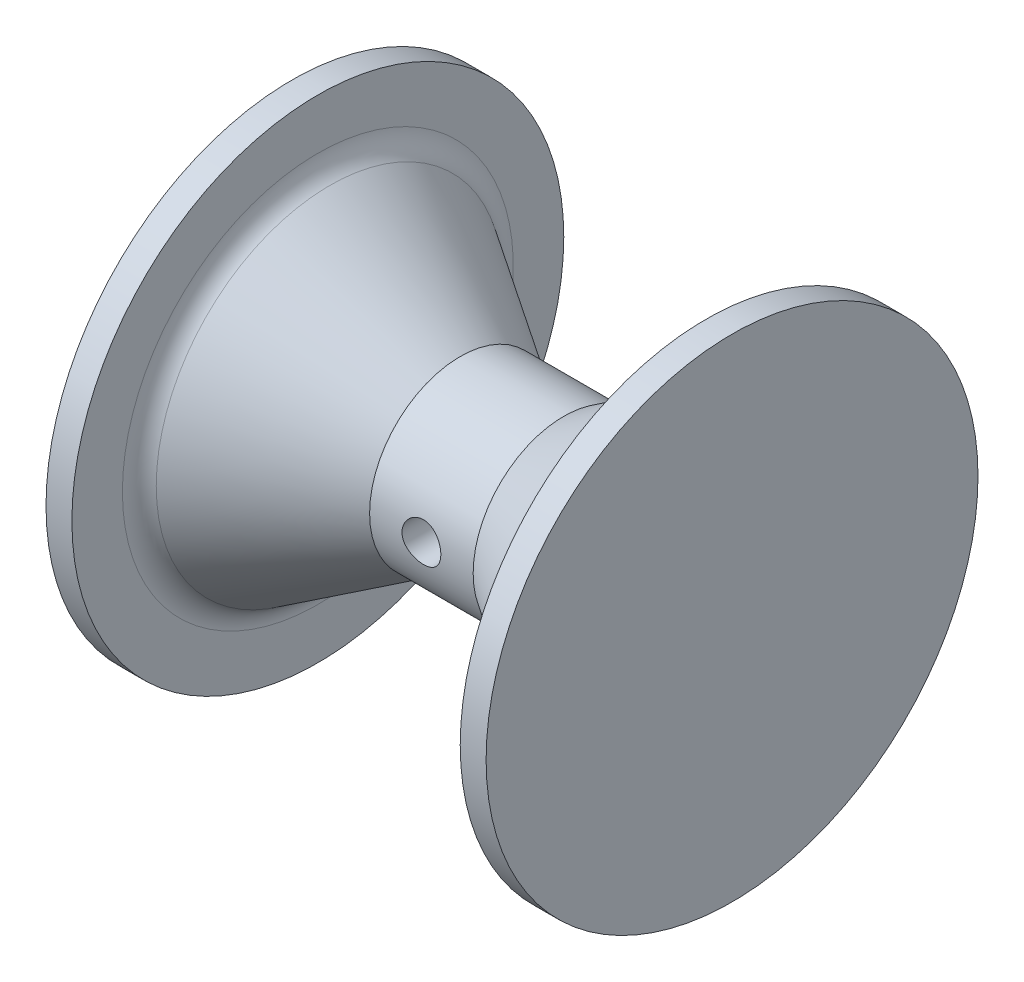
SolidWorks part; units mm, degrees
ref_plane "Front Plane" through (0, 0, 0) normal (0, 0, 1) x (1, 0, 0)
ref_plane "Top Plane" through (0, 0, 0) normal (0, 1, 0) x (1, 0, 0)
ref_plane "Right Plane" through (0, 0, 0) normal (1, 0, 0) x (0, 0, -1)
sketch "Sketch2" plane through (0, 0, 0) normal (0, 0, 1) x (1, 0, 0)
  line L0 (0, 0) -> (23.9161, 0) construction
  line L2 (0, 0) -> (0, 13.1643) construction
  line L3 (15, 14) -> (15, 19)
  line L4 (15, 19) -> (17, 19)
  line L5 (17, 19) -> (17, 0)
  line L6 (-4, 7) -> (4, 7)
  line L7 (4, 7) -> (15, 14)
  line L8 (-4, 7) -> (-15, 14)
  line L9 (-17, 19) -> (-17, 0)
  line L10 (-15, 19) -> (-17, 19)
  line L11 (-15, 14) -> (-15, 19)
  line L12 (-17, 0) -> (17, 0)
  dimension "D1" = 17
  dimension "D2" = 19
  dimension "D3" = 5
  dimension "D4" = 4
  dimension "D5" = 2
  dimension "D6" = 7
revolve "Revolve1" add sketch "Sketch2" angle 360 about L0
sketch "Sketch3" plane through (-17, 0, 0) normal (-1, 0, 0) x (0, 0, 1)
  line L0 (2.9, 1.5748) -> (2.9, -1.5748)
  arc A0 (2.9, 1.5748) -> (2.9, -1.5748) centre (0, 0) ccw
extrude "motor shaft" cut sketch "Sketch3" against normal blind 13
sketch "Sketch4" plane through (0, 0, 0) normal (0, 0, 1) x (1, 0, 0)
  circle A0 centre (0, 0) radius 1.5
  circle A1 centre (5, 0) radius 1.5 construction
  circle A2 centre (-5, 0) radius 1.5 construction
  dimension "D1" = 3
  dimension "D2" = 2
  dimension "D3" = 2
extrude "string holes" cut sketch "Sketch4" against normal mid plane 35
fillet "Fillet1" radius 2 2 edges at (-15, 0, 14) (15, 0, 14)
